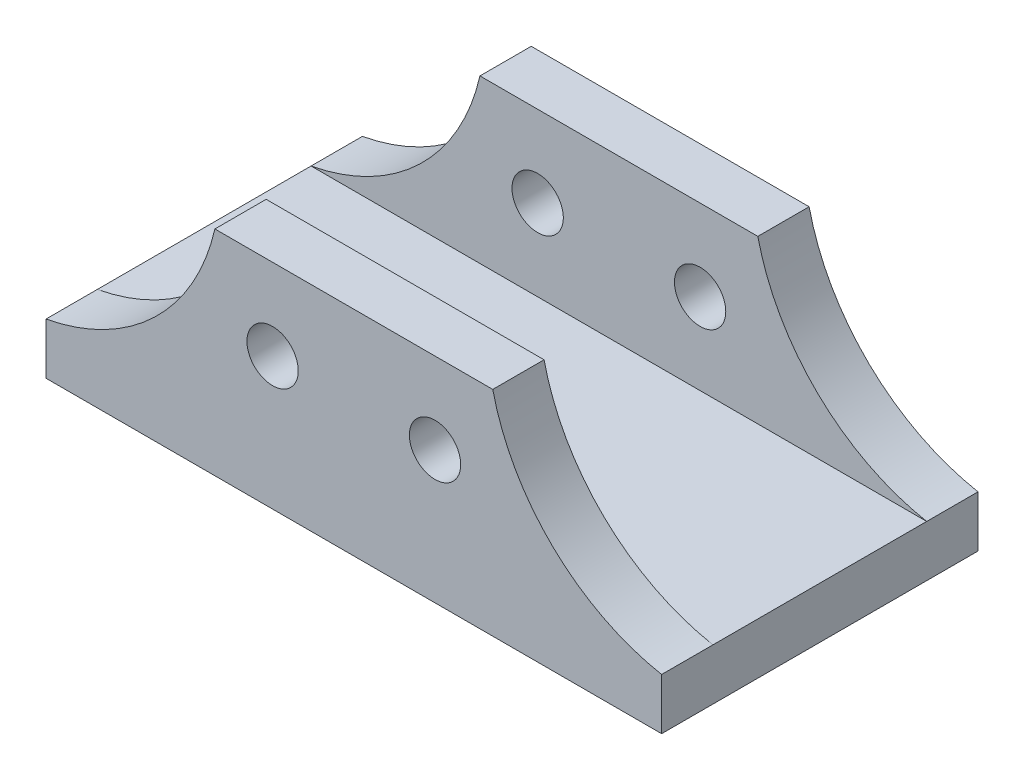
SolidWorks part; units mm, degrees
ref_plane "Front Plane" through (0, 0, 0) normal (0, 0, 1) x (1, 0, 0)
ref_plane "Top Plane" through (0, 0, 0) normal (0, 1, 0) x (1, 0, 0)
ref_plane "Right Plane" through (0, 0, 0) normal (1, 0, 0) x (0, 0, -1)
sketch "Sketch1" plane through (0, 0, 0) normal (0, 0, 1) x (1, 0, 0)
  line L0 (0, 50) -> (0, 0) construction
  line L1 (-72, 0) -> (72, 0)
  line L2 (72, 0) -> (72, 12)
  line L3 (-32.5, 50) -> (32.5, 50)
  line L4 (-72, 0) -> (-72, 12)
  arc A0 (72, 12) -> (32.5, 50) centre (81.2436, 61.1381) cw
  circle A1 centre (19, 31) radius 6
  circle A2 centre (-19, 31) radius 6
  arc A3 (-72, 12) -> (-32.5, 50) centre (-81.2436, 61.1381) ccw
  dimension "D5" = 50
  dimension "D6" = 12
  dimension "D1" = 72
  dimension "D2" = 12
  dimension "D3" = 32.5
  dimension "D4" = 50
  dimension "D7" = 31
  dimension "D8" = 19
extrude "Boss-Extrude1" add sketch "Sketch1" along normal blind 12
ref_plane "Plane1" through (0, 0, 37) normal (0, 0, 1) x (1, 0, 0)
mirror "Mirror2" about plane through (0, 0, 37) normal (0, 0, 1) of bodies 101
sketch "Sketch2" plane through (0, 0, 37) normal (0, 0, 1) x (1, 0, 0)
  line L1 (-72, 0) -> (72, 0)
  line L2 (-72, 0) -> (-72, 12)
  line L3 (-72, 12) -> (72, 12)
  line L4 (72, 0) -> (72, 12)
extrude "Boss-Extrude2" add sketch "Sketch2" along normal up to surface and the other way up to surface
